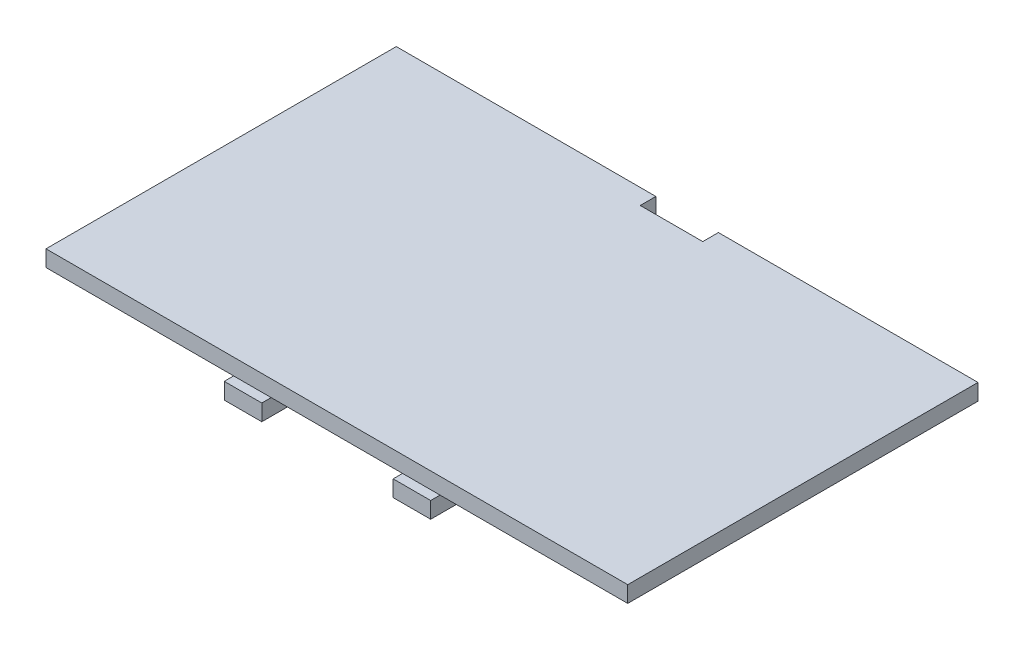
SolidWorks part; units mm, degrees
ref_plane "Alzado" through (0, 0, 0) normal (0, 0, 1) x (1, 0, 0)
ref_plane "Planta" through (0, 0, 0) normal (0, 1, 0) x (1, 0, 0)
ref_plane "Vista lateral" through (0, 0, 0) normal (1, 0, 0) x (0, 0, -1)
sketch "Croquis1" plane through (0, 0, 0) normal (0, 1, 0) x (1, 0, 0)
  line L1 (-46.5, -28) -> (46.5, -28)
  line L2 (-46.5, -28) -> (-46.5, 28)
  line L3 (-46.5, 28) -> (46.5, 28)
  line L4 (46.5, -28) -> (46.5, 28)
  line L5 (-46.5, -28) -> (46.5, 28) construction
  line L6 (-46.5, 28) -> (46.5, -28) construction
  point P0 (0, 0)
  dimension "D1" = 93
  dimension "D2" = 56
extrude "Saliente-Extruir1" add sketch "Croquis1" along normal blind 2.6
sketch "Croquis2" plane through (0, 2.6, 0) normal (0, 1, 0) x (1, 0, 0)
  line L0 (46.5, 28) -> (5, 28)
  line L1 (46.5, 28) -> (-46.5, 28) construction
  line L2 (5, 28) -> (5, 25.5)
  line L3 (5, 25.5) -> (-5, 25.5)
  line L4 (-5, 25.5) -> (-5, 28)
  line L5 (-5, 28) -> (5, 28)
  dimension "D1" = 41.5
  dimension "D2" = 2.5
  dimension "D3" = 10
extrude "Cortar-Extruir1" cut sketch "Croquis2" against normal blind 2.6 contours L2 L3 L4 L5
sketch "Croquis3" plane through (0, 0, 0) normal (0, -1, 0) x (1, 0, 0)
  line L0 (-16.5, 29.5) -> (-16.5, 25)
  line L1 (-46.5, 28) -> (46.5, 28) construction
  line L2 (16.5, 28) -> (16.5, 29.5)
  line L3 (16.5, 28) -> (16.5, 25)
  line L4 (16.5, 25) -> (10.5, 25)
  line L5 (10.5, 25) -> (10.5, 29.5)
  line L6 (10.5, 29.5) -> (16.5, 29.5)
  line L14 (-16.5, 29.5) -> (-10.5, 29.5)
  line L15 (-10.5, 29.5) -> (-10.5, 25)
  line L16 (-10.5, 25) -> (-16.5, 25)
  line M11 (46.5, 28) -> (-46.5, 28)
  dimension "D2" = 1.5
  dimension "D3" = 3
  dimension "D4" = 6
  dimension "D6" = 6
extrude "Saliente-Extruir2" add sketch "Croquis3" along normal blind 2.6 contours L6 L5 L2 M11 | L5 L4 L3 M11 | L15 L14 L0 M11 | L16 L15 L0 M11
